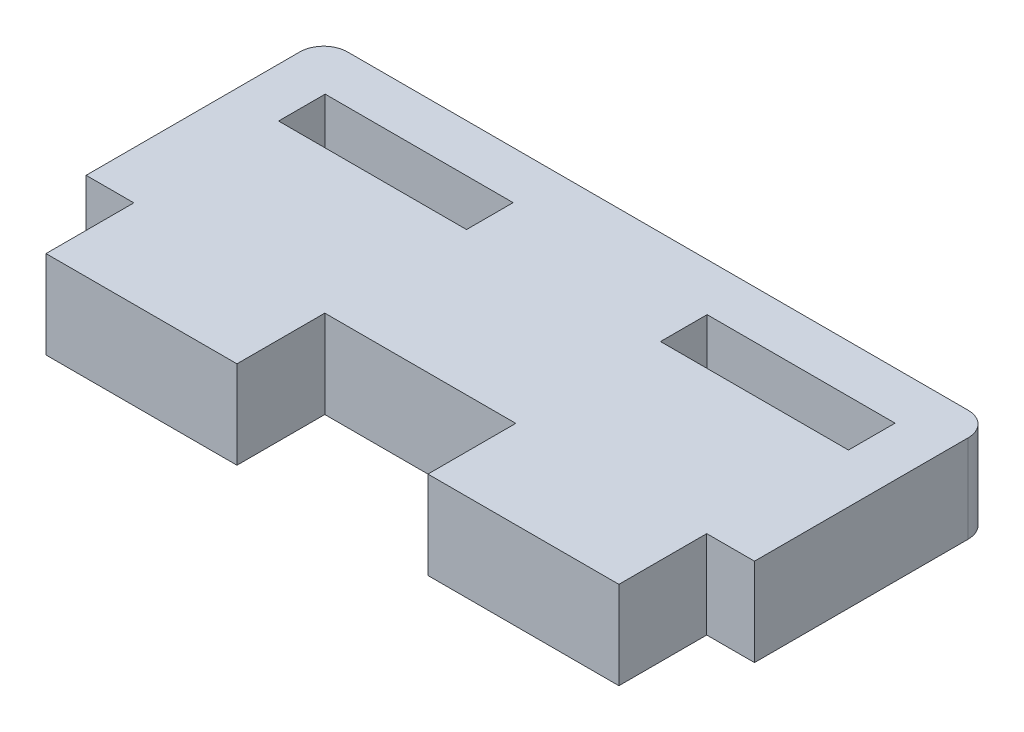
SolidWorks part; units mm, degrees
ref_plane "Front Plane" through (0, 0, 0) normal (0, 0, 1) x (1, 0, 0)
ref_plane "Top Plane" through (0, 0, 0) normal (0, 1, 0) x (1, 0, 0)
ref_plane "Right Plane" through (0, 0, 0) normal (1, 0, 0) x (0, 0, -1)
sketch "Sketch1" plane through (0, 0, 0) normal (0, 1, 0) x (1, 0, 0)
  line L0 (0, 4.7625) -> (0, -4.7625) construction
  line L1 (22.225, -4.7625) -> (19.05, -4.7625)
  line L2 (22.225, -4.7625) -> (22.225, 4.7625)
  line L3 (18.95, 4.7625) -> (6.45, 4.7625)
  line L4 (-22.225, -4.7625) -> (-22.225, 4.7625)
  line L5 (22.225, -4.7625) -> (-22.225, 4.7625) construction
  line L6 (22.225, 4.7625) -> (-22.225, -4.7625) construction
  line L7 (-6.35, -10.6045) -> (-19.05, -10.6045)
  line L8 (-6.35, -10.6045) -> (-6.35, -4.7625)
  line L9 (6.35, -4.7625) -> (-6.35, -4.7625)
  line L10 (-19.05, -10.6045) -> (-19.05, -4.7625)
  line L11 (-6.35, -10.6045) -> (-19.05, -4.7625) construction
  line L12 (-6.35, -4.7625) -> (-19.05, -10.6045) construction
  line L13 (-6.45, 7.8613) -> (-18.95, 7.8613)
  line L14 (6.45, 7.8613) -> (6.45, 4.7625)
  line L15 (6.35, -10.6045) -> (6.35, -4.7625)
  line L16 (-6.45, 7.8613) -> (-6.45, 4.7625)
  line L17 (6.45, 7.8613) -> (-6.45, 4.7625) construction
  line L18 (6.45, 4.7625) -> (-6.45, 7.8613) construction
  line L19 (18.95, 4.7625) -> (18.95, 7.8613)
  line L20 (-6.45, 4.7625) -> (-18.95, 4.7625)
  line L21 (-22.225, 4.7625) -> (-22.225, 7.8613)
  line L22 (19.05, -10.6045) -> (19.05, -4.7625)
  line L23 (-18.95, 4.7625) -> (-18.95, 7.8613)
  line L24 (6.35, -10.6045) -> (19.05, -10.6045)
  line L25 (22.225, 4.7625) -> (22.225, 7.8613)
  line L26 (22.225, 11.0363) -> (-22.225, 11.0363)
  line L27 (22.225, 11.0363) -> (22.225, 7.8613)
  line L28 (18.95, 7.8613) -> (6.45, 7.8613)
  line L29 (-22.225, 11.0363) -> (-22.225, 7.8613)
  line L30 (22.225, 11.0363) -> (-22.225, 7.8613) construction
  line L31 (22.225, 7.8613) -> (-22.225, 11.0363) construction
  line L32 (-19.05, -4.7625) -> (-22.225, -4.7625)
  point P0 (0, 0)
  point P6 (-12.7, -7.6835)
  point P11 (0, 6.3119)
  point P24 (0, 9.4488)
  dimension "D1" = 44.45
  dimension "D2" = 9.525
  dimension "D3" = 3.0988
  dimension "D4" = 12.9
  dimension "D5" = 3.0988
  dimension "D6" = 3.275
  dimension "D7" = 3.175
  dimension "D8" = 5.842
  dimension "D9" = 12.7
  dimension "D10" = 12.7
extrude "Boss-Extrude1" add sketch "Sketch1" along normal blind 5.842
fillet "Fillet1" radius 1.5875 2 edges at (22.225, 2.921, -11.0363) (-22.225, 2.921, -11.0363)
